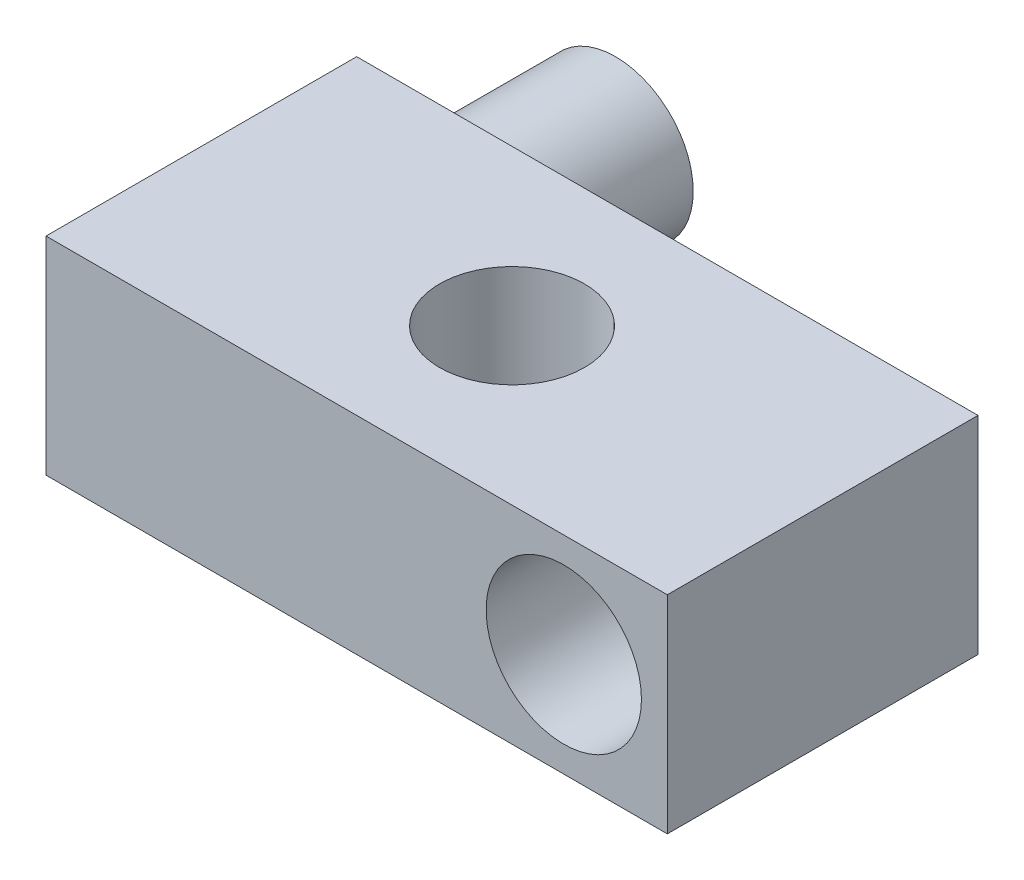
SolidWorks part; units mm, degrees
ref_plane "Front" through (0, 0, 0) normal (0, 0, 1) x (1, 0, 0)
ref_plane "Top" through (0, 0, 0) normal (0, 1, 0) x (1, 0, 0)
ref_plane "Right" through (0, 0, 0) normal (1, 0, 0) x (0, 0, -1)
sketch "Эскиз1" plane through (0, 0, 0) normal (0, 0, 1) x (1, 0, 0)
  line L0 (10.9582, 0.498) -> (-1.0418, 0.498) construction
  line L1 (10.9582, -1.502) -> (-1.0418, -1.502)
  line L2 (10.9582, -1.502) -> (10.9582, 2.498)
  line L3 (10.9582, 2.498) -> (-1.0418, 2.498)
  line L4 (-1.0418, -1.502) -> (-1.0418, 2.498)
  circle A0 centre (8.9582, 0.498) radius 1.5
  point P8 (0, 0)
  dimension "D1" = 2
  dimension "D3" = 4
  dimension "D2" = 12
extrude "Бобышка-Вытянуть1" add sketch "Эскиз1" along normal blind 6
sketch "Эскиз2" plane through (0, 0, 0) normal (0, 0, -1) x (-1, 0, 0)
  line L0 (1.0418, 2.498) -> (1.0418, -1.502) construction
  circle A0 centre (-0.9582, 0.498) radius 1.5
  dimension "D1" = 2
extrude "Бобышка-Вытянуть2" add sketch "Эскиз2" along normal blind 3
sketch "Эскиз3" plane through (0, -1.502, 0) normal (0, -1, 0) x (1, 0, 0)
  circle A0 centre (4.9582, 3) radius 1.4
extrude "Вырез-Вытянуть1" cut sketch "Эскиз3" against normal up to next
